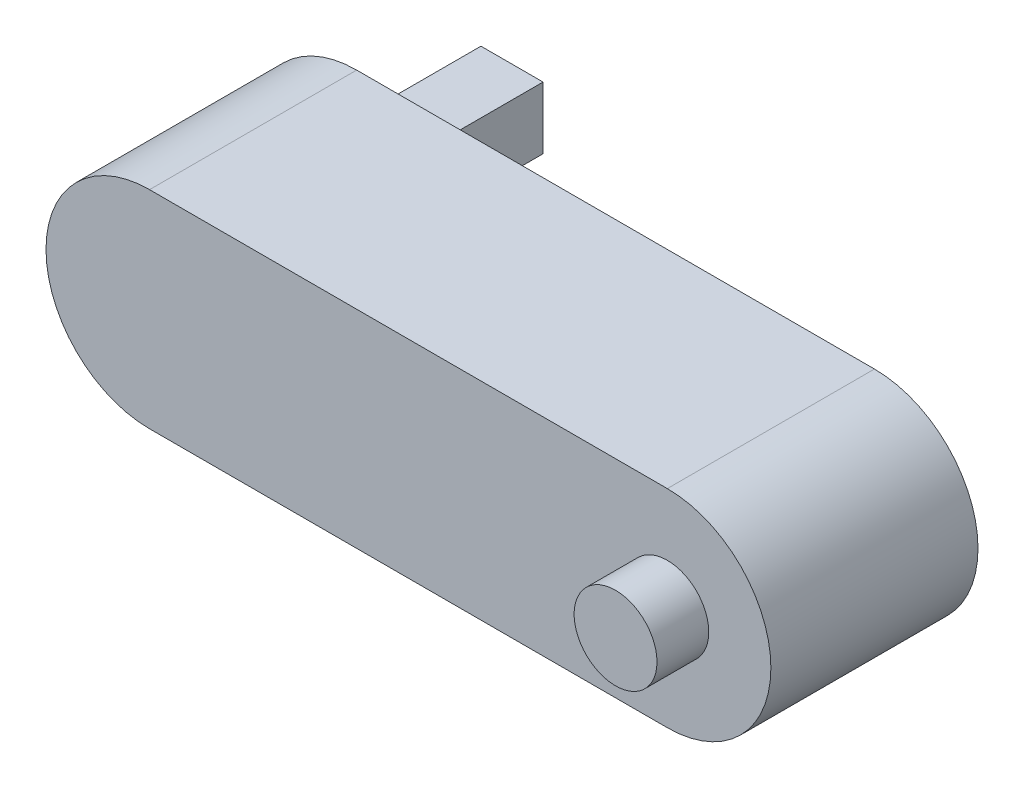
SolidWorks part; units mm, degrees
ref_plane "前视基准面" through (0, 0, 0) normal (0, 0, 1) x (1, 0, 0)
ref_plane "上视基准面" through (0, 0, 0) normal (0, 1, 0) x (1, 0, 0)
ref_plane "右视基准面" through (0, 0, 0) normal (1, 0, 0) x (0, 0, -1)
other "Configuration Table"
sketch "草图1" plane through (0, 0, 0) normal (0, 0, 1) x (1, 0, 0)
  line L0 (0, 0) -> (50, 0) construction
  line L1 (0, 10) -> (50, 10)
  line L2 (0, -10) -> (50, -10)
  arc A0 (0, 10) -> (0, -10) centre (0, 0) ccw
  arc A1 (50, -10) -> (50, 10) centre (50, 0) ccw
  point P3 (25, 0)
  dimension "D2" = 10
  dimension "D1" = 50
extrude "凸台-拉伸1" add sketch "草图1" along normal blind 20
sketch "草图2" plane through (0, 0, 20) normal (0, 0, 1) x (1, 0, 0)
  circle A0 centre (0, 0) radius 4
  circle A1 centre (50, 0) radius 4
  dimension "D1" = 8
extrude "凸台-拉伸2" add sketch "草图2" along normal blind 5 contours A1
sketch "草图3" plane through (0, 0, 0) normal (0, 0, -1) x (-1, 0, 0)
  line L1 (-3, -3) -> (3, -3)
  line L2 (-3, -3) -> (-3, 3)
  line L3 (-3, 3) -> (3, 3)
  line L4 (3, -3) -> (3, 3)
  line L5 (-3, -3) -> (3, 3) construction
  line L6 (-3, 3) -> (3, -3) construction
  point P0 (0, 0)
  dimension "D1" = 6
  dimension "D2" = 6
extrude "凸台-拉伸3" add sketch "草图3" along normal blind 15
